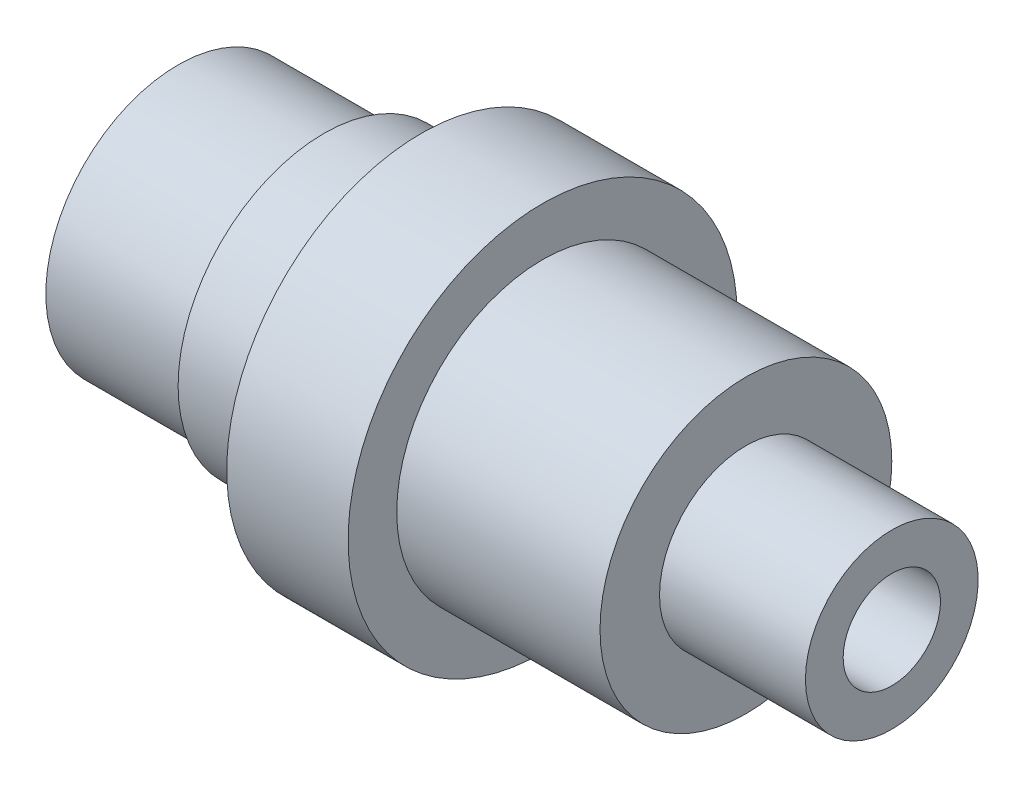
SolidWorks part; units mm, degrees
ref_plane "Front Plane" through (0, 0, 0) normal (0, 0, 1) x (1, 0, 0)
ref_plane "Top Plane" through (0, 0, 0) normal (0, 1, 0) x (1, 0, 0)
ref_plane "Right Plane" through (0, 0, 0) normal (1, 0, 0) x (0, 0, -1)
sketch "Sketch1" plane through (0, 0, 0) normal (1, 0, 0) x (0, 0, -1)
  circle A0 centre (0, 0) radius 12.7
  dimension "D1" = 25.4
extrude "Boss-Extrude1" add sketch "Sketch1" along normal blind 7.9248
sketch "Sketch2" plane through (7.9248, 0, 0) normal (1, 0, 0) x (0, 0, -1)
  circle A0 centre (0, 0) radius 9.525
  dimension "D1" = 19.05
extrude "Boss-Extrude2" add sketch "Sketch2" along normal blind 13.2715
sketch "Sketch3" plane through (21.1963, 0, 0) normal (1, 0, 0) x (0, 0, -1)
  circle A0 centre (0, 0) radius 5.6388
  dimension "D1" = 11.2776
extrude "Boss-Extrude3" add sketch "Sketch3" along normal blind 9.525
sketch "Sketch4" plane through (0, 0, 0) normal (-1, 0, 0) x (0, 0, 1)
  circle A0 centre (0, 0) radius 9.525
  dimension "D1" = 19.05
extrude "Boss-Extrude4" add sketch "Sketch4" along normal blind 6.35
sketch "Sketch5" plane through (-6.35, 0, 0) normal (-1, 0, 0) x (0, 0, 1)
  circle A0 centre (0, 0) radius 8.636
  dimension "D1" = 17.272
extrude "Boss-Extrude5" add sketch "Sketch5" along normal blind 9.525
sketch "Sketch6" plane through (-15.875, 0, 0) normal (-1, 0, 0) x (0, 0, 1)
  circle A0 centre (0, 0) radius 6.35
  dimension "D1" = 12.7
extrude "Cut-Extrude1" cut sketch "Sketch6" against normal blind 25.4
sketch "Sketch7" plane through (9.525, 0, 0) normal (-1, 0, 0) x (0, 0, 1)
  circle A0 centre (0, 0) radius 3.175
  dimension "D1" = 6.35
extrude "Cut-Extrude2" cut sketch "Sketch7" against normal through all
